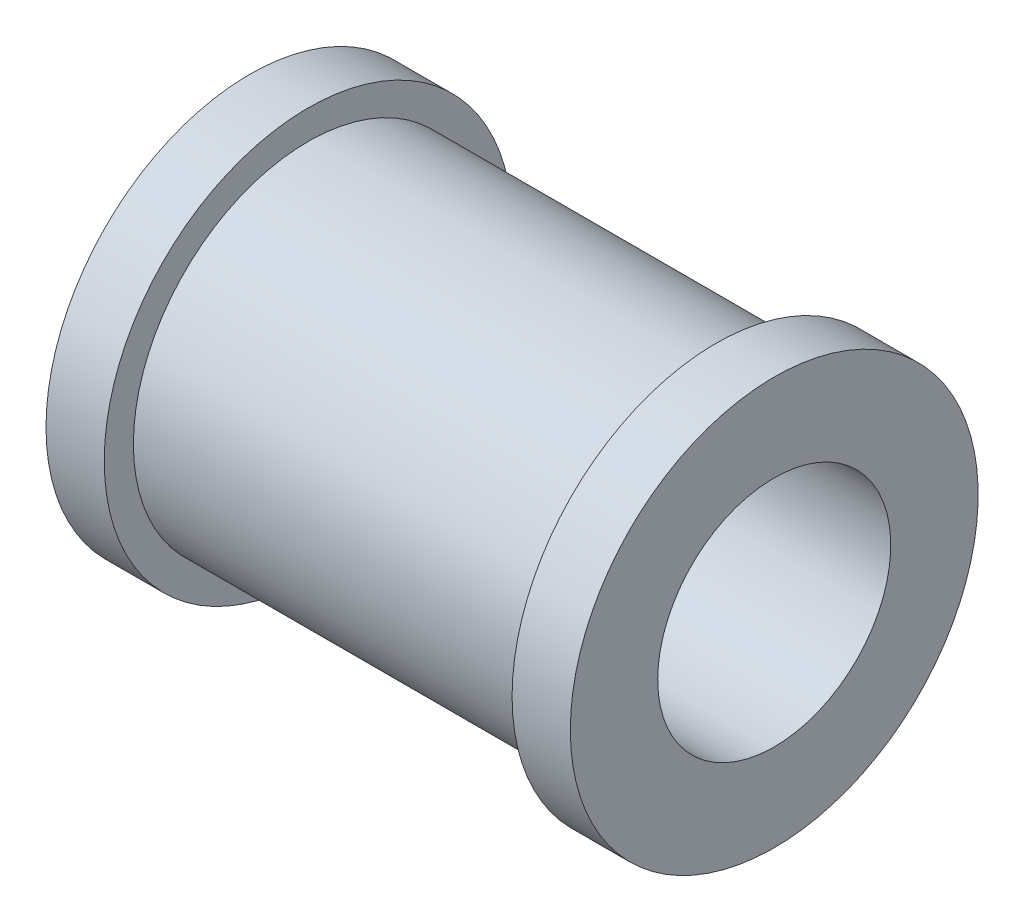
SolidWorks part; units mm, degrees
ref_plane "Front Plane" through (0, 0, 0) normal (0, 0, 1) x (1, 0, 0)
ref_plane "Top Plane" through (0, 0, 0) normal (0, 1, 0) x (1, 0, 0)
ref_plane "Right Plane" through (0, 0, 0) normal (1, 0, 0) x (0, 0, -1)
sketch "Sketch1" plane through (0, 0, 0) normal (0, 0, 1) x (1, 0, 0)
  line L0 (0, 0) -> (18, 0) construction
  line L1 (0, 4) -> (0, 7)
  line L2 (0, 7) -> (2, 7)
  line L3 (2, 7) -> (2, 6)
  line L4 (2, 6) -> (16, 6)
  line L5 (16, 6) -> (16, 7)
  line L6 (16, 7) -> (18, 7)
  line L7 (18, 7) -> (18, 4)
  line L8 (0, 4) -> (18, 4)
  dimension "D1" = 18
  dimension "D2" = 7
  dimension "D3" = 7
  dimension "D4" = 6
  dimension "D5" = 2
  dimension "D6" = 2
  dimension "D7" = 4
revolve "Revolve2" add sketch "Sketch1" angle 360 about L0
